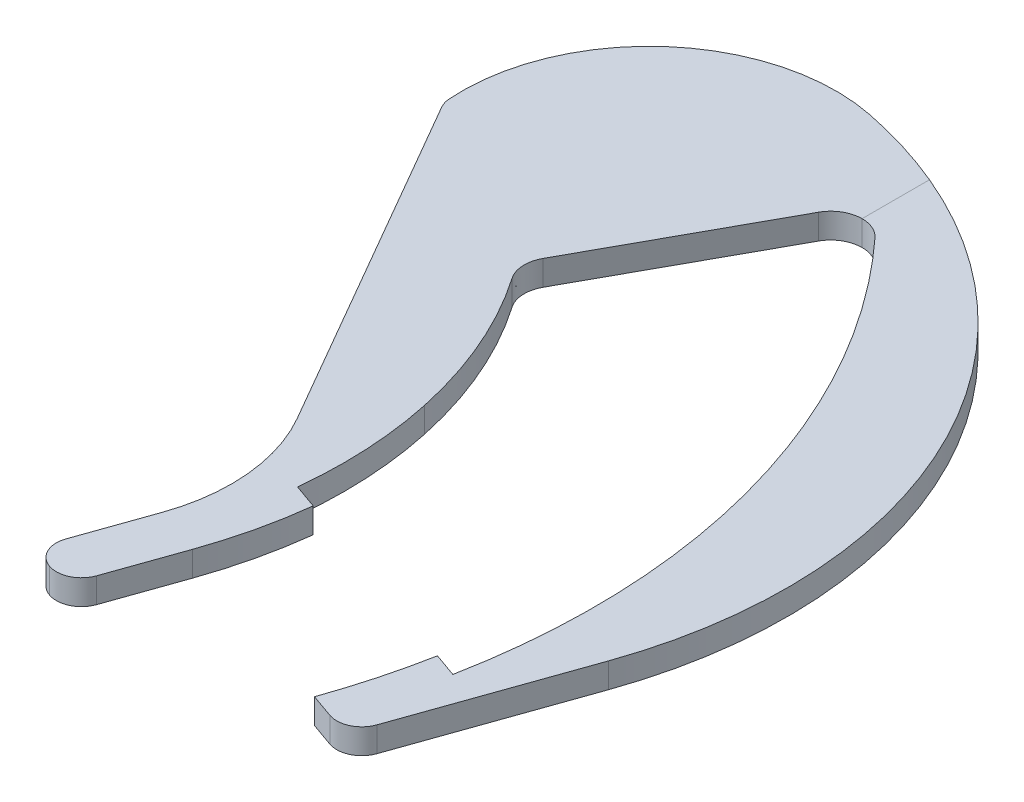
SolidWorks part; units mm, degrees
material "Acrylic (Medium-high impact)"
ref_plane "Front Plane" through (0, 0, 0) normal (0, 0, 1) x (1, 0, 0)
ref_plane "Top Plane" through (0, 0, 0) normal (0, 1, 0) x (1, 0, 0)
ref_plane "Right Plane" through (0, 0, 0) normal (1, 0, 0) x (0, 0, -1)
sketch "Sketch1" plane through (0, 0, 0) normal (0, 1, 0) x (1, 0, 0)
  line L59 (-47.4532, 53.4043) -> (-98.2532, 141.3925)
  line L60 (0, 0) -> (27.9445, -9.8615)
  line L61 (0, 0) -> (-43.9505, 15.5099)
  line L62 (-1000, 0) -> (49000, 0) construction
  line L64 (27.9445, -9.8615) -> (72.8551, -25.7103) construction
  line L65 (72.8551, -25.7103) -> (88.7038, 19.2003) construction
  line L66 (27.9445, -9.8615) -> (-207.1917, -676.1663) construction
  line L67 (45.3803, 39.5461) -> (27.9445, -9.8615)
  line L68 (-43.9505, 15.5099) -> (-28.1017, 60.4205) construction
  line L69 (-88.861, 31.3587) -> (-86.5095, 38.0222) construction
  line L70 (53.7407, 188.0768) -> (-24.6782, 188.0768) construction
  line L71 (-43.9505, 15.5099) -> (-88.861, 31.3587) construction
  arc A0 (45.3803, 39.5461) -> (-41.5665, 192.8393) centre (-64.7226, 78.401) ccw
  arc A1 (-98.2532, 141.3925) -> (-41.5665, 192.8393) centre (-50.9898, 146.2689) cw
  arc A2 (-43.9505, 15.5099) -> (-47.4532, 53.4043) centre (-86.8603, 30.6526) ccw
  dimension "D5" = 4.7625
  dimension "D2" = 45.5033
  dimension "D11" = 37.8944
  dimension "D12" = 7.0663
  dimension "D8" = 52.3939
  dimension "D9" = 46.6069
  dimension "D4" = 19.438
  dimension "D7" = 116.7576
  dimension "D6" = 47.5143
  dimension "D10" = 29.6335
  dimension "D3" = 101.6
  dimension "D1" = 47.625
  dimension "D13" = 78.4189
extrude "Boss-Extrude1" add sketch "Sketch1" along normal blind 6.35
ref_plane "Plane1" through (-8.003, 0, -2.8242) normal (0.943, 0, 0.3328) x (0.3328, 0, -0.943)
sketch "Sketch2" plane through (0, 0, 0) normal (0, 1, 0) x (1, 0, 0)
  line L0 (-43.9505, 15.5099) -> (27.9445, -9.8615) construction
  point P2 (-8.003, 2.8242)
  point P3 (-8.003, 2.8242)
  line B0 (-29.2366, 81.4276) -> (15.5744, 98.7927)
  line B1 (11.6131, 92.147) -> (-21.6985, 79.2205)
  line B2 (-25.5648, 59.5252) -> (22.719, 42.4861)
  line B3 (28.6163, 16.8366) -> (22.5595, 18.974)
  line B4 (-26.1738, 36.1718) -> (-32.322, 38.3415)
  line B5 (-25.1489, 88.1192) -> (10.3796, 101.8872)
  line B6 (-51.3926, 119.7839) -> (-26.6046, 164.8774)
  line B7 (-44.0739, 123.2114) -> (-25.3, 157.3642)
  line B8 (-31.9553, 11.2769) -> (15.9493, -5.6285)
  line B9 (22.5595, 18.974) -> (-26.1738, 36.1718)
  arc B10 (-27.5994, 72.1341) -> (-28.8269, 77.6086) centre (-28.1238, 74.8914) ccw
  arc B11 (-29.2366, 81.4276) -> (-29.7842, 81.1914) centre (-26.3685, 74.0264) ccw
  arc B12 (17.8172, 99.3043) -> (15.5744, 98.7927) centre (18.4425, 91.3914) ccw
  arc B13 (18.8456, 95.8956) -> (20.3121, 90.5015) centre (19.3312, 93.1313) ccw
  arc B14 (13.6735, 91.1895) -> (20.9914, 87.3846) centre (19.3312, 93.1313) ccw
  arc B15 (-27.0229, 69.0118) -> (-22.587, 77.1552) centre (-28.1238, 74.8914) ccw
  arc B16 (20.3121, 90.5015) -> (18.8456, 95.8956) centre (19.3312, 93.1313) ccw
  arc B17 (28.6163, 16.8366) -> (26.1201, 93.4056) centre (-140.6727, 49.6428) ccw
  arc B18 (26.9496, 45.3998) -> (22.9664, 86.2145) centre (-140.6737, 49.643) ccw
  arc B19 (-28.827, 77.6085) -> (-27.5994, 72.1341) centre (-28.1238, 74.8914) ccw
  arc B20 (-27.6639, 62.1695) -> (-25.8173, 59.6267) centre (-24.5082, 62.5193) ccw
  arc B21 (-32.322, 38.3415) -> (-34.1314, 72.3702) centre (-140.6727, 49.6428) ccw
  arc B22 (10.3796, 101.8872) -> (14.8753, 112.2511) centre (7.5115, 109.2884) ccw
  arc B23 (-35.3684, 92.527) -> (-25.1489, 88.1192) centre (-28.017, 95.5204) ccw
  arc B24 (-43.0735, 110.8831) -> (-43.464, 121.0781) centre (-46.3902, 115.8611) ccw
  arc B25 (15.9493, -5.6285) -> (22.5595, 18.974) centre (-140.6729, 49.642) ccw
  arc B26 (-31.9553, 11.2769) -> (-26.1738, 36.1718) centre (-140.6725, 49.6436) ccw
  spline B27 degree 3 poles (17.8172, 99.3043) (18.2808, 99.3409) (18.7407, 99.3366) (19.6534, 99.2495) (20.1077, 99.1662) (21.0026, 98.9191) (21.4331, 98.7584) (22.0543, 98.4634) (22.2573, 98.356) (22.6549, 98.123) (22.8504, 97.9967) (23.4171, 97.5941) (23.7667, 97.2963) (24.2502, 96.807) (24.4045, 96.6367) (24.699, 96.2816) (24.84, 96.0958) (25.2347, 95.5249) (25.4616, 95.126) (25.8451, 94.2925) (26.0022, 93.8555) (26.1202, 93.4057) knots 0 0 0 0 0.125 0.125 0.25 0.25 0.375 0.375 0.4375 0.4375 0.5 0.5 0.625 0.625 0.6875 0.6875 0.75 0.75 0.875 0.875 1 1 1 1
  spline B28 degree 3 poles (-34.1313, 72.3702) (-34.3175, 73.2427) (-34.3554, 74.1214) (-34.1352, 75.8909) (-33.8828, 76.7344) (-33.0952, 78.3332) (-32.5797, 79.0482) (-31.6292, 79.9869) (-31.2886, 80.2706) (-30.5679, 80.7764) (-30.1868, 80.9994) (-29.7842, 81.1914) knots 0 0 0 0 0.25 0.25 0.5 0.5 0.75 0.75 0.875 0.875 1 1 1 1
  spline B29 degree 2 poles (-26.6046, 164.8774) (-26.1506, 165.7033) (-25.5154, 166.4003) (-24.879, 167.0987) (-24.0954, 167.6288) (-23.3138, 168.1575) (-22.4289, 168.4884) (-21.5475, 168.8181) (-20.6123, 168.9325) (-19.6749, 169.0473) (-18.7356, 168.9385) (-17.7973, 168.83) (-16.9097, 168.5037) (-16.0263, 168.179) (-15.2426, 167.656) (-14.4528, 167.129) (-13.8094, 166.4302) knots 0 0 0 0.125 0.125 0.25 0.25 0.375 0.375 0.5 0.5 0.625 0.625 0.75 0.75 0.875 0.875 1 1 1
  spline B30 degree 3 poles (26.1163, 93.4018) (24.3249, 100.238) (22.1302, 106.9013) (16.9621, 119.8936) (13.988, 126.2224) (9.777, 133.9217) (8.91, 135.4509) (7.1262, 138.488) (6.208, 139.9978) (3.3864, 144.4804) (1.4239, 147.3946) (-4.7015, 155.9203) (-9.1008, 161.3163) (-13.8094, 166.4302) knots 0 0 0 0 0.25 0.25 0.5 0.5 0.5625 0.5625 0.625 0.625 0.75 0.75 1 1 1 1
  spline B31 degree 3 poles (-13.3161, 158.7044) (-10.6959, 155.6457) (-8.187, 152.4937) (-4.3894, 147.3517) (-3.0295, 145.4278) (-0.3835, 141.5096) (0.9037, 139.513) (3.3926, 135.4673) (4.5925, 133.4211) (6.8969, 129.2936) (8.0024, 127.2107) (11.1817, 120.9021) (13.1195, 116.615) (14.8753, 112.2511) knots 0.074143 0.074143 0.074143 0.074143 0.222946 0.222946 0.309438 0.309438 0.395929 0.395929 0.48242 0.48242 0.568911 0.568911 0.741894 0.741894 0.741894 0.741894
  spline B32 degree 3 poles (-35.3684, 92.527) (-36.6307, 95.6269) (-38.0226, 98.6534) (-40.7885, 104.036) (-42.1249, 106.4194) (-43.5456, 108.7522) knots 0.447067 0.447067 0.447067 0.447067 0.670186 0.670186 0.854821 0.854821 0.854821 0.854821
  spline B33 degree 2 poles (-50.9715, 111.4537) (-51.5973, 112.3613) (-51.9523, 113.4056) (-52.3075, 114.4507) (-52.3641, 115.5542) (-52.4206, 116.6572) (-52.1734, 117.7348) (-51.9261, 118.8136) (-51.3926, 119.7839) knots 0 0 0 0.25 0.25 0.5 0.5 0.75 0.75 1 1 1
  spline B34 degree 3 poles (-50.9715, 111.4537) (-48.9588, 108.5346) (-47.0926, 105.5237) (-43.6539, 99.3178) (-42.0816, 96.1226) (-39.9504, 91.1875) (-39.2781, 89.5185) (-38.0214, 86.161) (-37.4355, 84.4688) (-36.3479, 81.058) (-35.8463, 79.3393) (-34.9276, 75.8754) (-34.5102, 74.1291) (-34.136, 72.3718) knots 0 0 0 0 0.25 0.25 0.5 0.5 0.625 0.625 0.75 0.75 0.875 0.875 1 1 1 1
sketch_block_instance "Ramp Geometry-1"
sketch_block "Ramp Geometry"
sketch "Sketch5" plane through (0, 6.35, 0) normal (0, 1, 0) x (1, 0, 0)
  line L1 (28.6163, 16.8366) -> (22.5595, 18.974) construction
  line L2 (-31.9553, 11.2769) -> (15.9493, -5.6285) construction
  line L3 (-26.1738, 36.1718) -> (-32.322, 38.3415) construction
  line L4 (-29.2366, 81.4276) -> (15.5744, 98.7927)
  line L5 (28.6163, 16.8366) -> (22.5595, 18.974)
  line L6 (-31.9553, 11.2769) -> (15.9493, -5.6285)
  line L7 (-26.1738, 36.1718) -> (-32.322, 38.3415)
  arc A2 (28.6163, 16.8366) -> (26.1201, 93.4056) centre (-140.6727, 49.6428) ccw construction
  arc A3 (15.9493, -5.6285) -> (22.5595, 18.974) centre (-140.6729, 49.642) ccw construction
  arc A4 (-31.9553, 11.2769) -> (-26.1738, 36.1718) centre (-140.6725, 49.6436) ccw construction
  arc A5 (-32.322, 38.3415) -> (-34.1314, 72.3702) centre (-140.6727, 49.6428) ccw construction
  arc A6 (-34.1314, 72.3702) -> (-29.2366, 81.4276) centre (-26.3759, 74.0303) cw
  arc A7 (26.1201, 93.4056) -> (15.5744, 98.7927) centre (18.4429, 91.3925) ccw
  arc A8 (28.6163, 16.8366) -> (26.1201, 93.4056) centre (-140.6727, 49.6428) ccw
  arc A9 (15.9493, -5.6285) -> (22.5595, 18.974) centre (-140.6729, 49.642) ccw
  arc A10 (-31.9553, 11.2769) -> (-26.1738, 36.1718) centre (-140.6725, 49.6436) ccw
  arc A11 (-32.322, 38.3415) -> (-34.1314, 72.3702) centre (-140.6727, 49.6428) ccw
  spline S2 degree 3 poles (17.8172, 99.3043) (18.2808, 99.3409) (18.7407, 99.3366) (19.6534, 99.2495) (20.1077, 99.1662) (21.0026, 98.9191) (21.4331, 98.7584) (22.0543, 98.4634) (22.2573, 98.356) (22.6549, 98.123) (22.8504, 97.9967) (23.4171, 97.5941) (23.7667, 97.2963) (24.2502, 96.807) (24.4045, 96.6367) (24.699, 96.2816) (24.84, 96.0958) (25.2347, 95.5249) (25.4616, 95.126) (25.8451, 94.2925) (26.0022, 93.8555) (26.1202, 93.4057) knots 0 0 0 0 0.125 0.125 0.25 0.25 0.375 0.375 0.4375 0.4375 0.5 0.5 0.625 0.625 0.6875 0.6875 0.75 0.75 0.875 0.875 1 1 1 1 construction
  spline S3 degree 3 poles (-34.1313, 72.3702) (-34.3175, 73.2427) (-34.3554, 74.1214) (-34.1352, 75.8909) (-33.8828, 76.7344) (-33.0952, 78.3332) (-32.5797, 79.0482) (-31.6292, 79.9869) (-31.2886, 80.2706) (-30.5679, 80.7764) (-30.1868, 80.9994) (-29.7842, 81.1914) knots 0 0 0 0 0.25 0.25 0.5 0.5 0.75 0.75 0.875 0.875 1 1 1 1 construction
extrude "Cut-Extrude1" cut sketch "Sketch5" against normal through all
sketch "Sketch6" plane through (0, 6.35, 0) normal (0, 1, 0) x (1, 0, 0)
  line L0 (-34.136, 72.3718) -> (26.1163, 93.4018)
  line L2 (-51.3926, 119.7839) -> (-26.6046, 164.8774) construction
  line L3 (-51.3926, 119.7839) -> (-26.6046, 164.8774)
  spline S0 degree 3 poles (-1429.6439, -1247.1312) (-221.2393, -482.3872) (103.2117, -96.9361) (16.9621, 119.8936) (13.988, 126.2224) (9.777, 133.9217) (8.91, 135.4509) (7.1262, 138.488) (6.208, 139.9978) (3.3864, 144.4804) (1.4239, 147.3946) (-186.5695, 409.0534) (-1027.0588, 71.2021) (-1932.3264, -325.7002) knots -7.844512 -7.844512 -7.844512 -7.844512 0.25 0.25 0.5 0.5 0.5625 0.5625 0.625 0.625 0.75 0.75 12.134027 12.134027 12.134027 12.134027 only from (26.1163, 93.4018) to (-13.8094, 166.4302) construction
  spline S1 degree 2 poles (1493.7423, -1132.5068) (-85.9486, 100.0778) (-25.5154, 166.4003) (-24.879, 167.0987) (-24.0954, 167.6288) (-23.3138, 168.1575) (-22.4289, 168.4884) (-21.5475, 168.8181) (-20.6123, 168.9325) (-19.6749, 169.0473) (-18.7356, 168.9385) (-17.7973, 168.83) (-16.9097, 168.5037) (-16.0263, 168.179) (-15.2426, 167.656) (59.3198, 117.902) (-1170.3473, -1463.6448) knots -11.768568 -11.768568 -11.768568 0.125 0.125 0.25 0.25 0.375 0.375 0.5 0.5 0.625 0.625 0.75 0.75 0.875 0.875 12.67723 12.67723 12.67723 only from (-26.6046, 164.8774) to (-13.8094, 166.4302) construction
  spline S2 degree 2 poles (1805.4899, 851.8486) (-23.0142, 28.2719) (-51.9523, 113.4056) (-52.3075, 114.4507) (-52.3641, 115.5542) (-52.4206, 116.6572) (-52.1734, 117.7348) (-32.0934, 205.297) (1872.6772, -421.0496) knots -20.129916 -20.129916 -20.129916 0.25 0.25 0.5 0.5 0.75 0.75 21.042954 21.042954 21.042954 only from (-50.9715, 111.4537) to (-51.3926, 119.7839) construction
  spline S3 degree 3 poles (-1984.765, -331.989) (-829.3418, 131.8338) (-152.4686, 295.6978) (-43.6539, 99.3178) (-42.0816, 96.1226) (-39.9504, 91.1875) (-39.2781, 89.5185) (-38.0214, 86.161) (-37.4355, 84.4688) (-36.3479, 81.058) (-35.8463, 79.3393) (3.3124, -68.2971) (-256.1389, -315.9435) (-1530.5486, 1352.6355) knots -15.321981 -15.321981 -15.321981 -15.321981 0.25 0.25 0.5 0.5 0.625 0.625 0.75 0.75 0.875 0.875 11.405236 11.405236 11.405236 11.405236 only from (-50.9715, 111.4537) to (-34.136, 72.3718) construction
  spline S4 degree 3 poles (26.1163, 93.4018) (24.3249, 100.238) (22.1302, 106.9013) (16.9621, 119.8936) (13.988, 126.2224) (9.777, 133.9217) (8.91, 135.4509) (7.1262, 138.488) (6.208, 139.9978) (3.3864, 144.4804) (1.4239, 147.3946) (-4.7015, 155.9203) (-9.1008, 161.3163) (-13.8094, 166.4302) knots 0 0 0 0 0.25 0.25 0.5 0.5 0.5625 0.5625 0.625 0.625 0.75 0.75 1 1 1 1
  spline S5 degree 2 poles (-26.6046, 164.8774) (-26.1506, 165.7033) (-25.5154, 166.4003) (-24.879, 167.0987) (-24.0954, 167.6288) (-23.3138, 168.1575) (-22.4289, 168.4884) (-21.5475, 168.8181) (-20.6123, 168.9325) (-19.6749, 169.0473) (-18.7356, 168.9385) (-17.7973, 168.83) (-16.9097, 168.5037) (-16.0263, 168.179) (-15.2426, 167.656) (-14.4528, 167.129) (-13.8094, 166.4302) knots 0 0 0 0.125 0.125 0.25 0.25 0.375 0.375 0.5 0.5 0.625 0.625 0.75 0.75 0.875 0.875 1 1 1
  spline S6 degree 2 poles (-50.9715, 111.4537) (-51.5973, 112.3613) (-51.9523, 113.4056) (-52.3075, 114.4507) (-52.3641, 115.5542) (-52.4206, 116.6572) (-52.1734, 117.7348) (-51.9261, 118.8136) (-51.3926, 119.7839) knots 0 0 0 0.25 0.25 0.5 0.5 0.75 0.75 1 1 1
  spline S7 degree 3 poles (-50.9715, 111.4537) (-48.9588, 108.5346) (-47.0926, 105.5237) (-43.6539, 99.3178) (-42.0816, 96.1226) (-39.9504, 91.1875) (-39.2781, 89.5185) (-38.0214, 86.161) (-37.4355, 84.4688) (-36.3479, 81.058) (-35.8463, 79.3393) (-34.9276, 75.8754) (-34.5102, 74.1291) (-34.136, 72.3718) knots 0 0 0 0 0.25 0.25 0.5 0.5 0.625 0.625 0.75 0.75 0.875 0.875 1 1 1 1
extrude "Cut-Extrude2" cut sketch "Sketch6" against normal through all
sketch "Sketch7" plane through (0, 0, 0) normal (0, 1, 0) x (1, 0, 0)
  line L0 (-43.9505, 15.5099) -> (-52.4031, -8.4424)
  line L1 (-52.4031, -8.4424) -> (-40.4081, -12.6754)
  line L2 (-40.4081, -12.6754) -> (-31.9553, 11.2769)
  line L3 (-31.9553, 11.2769) -> (-43.9505, 15.5099)
  arc A0 (-31.9553, 11.2769) -> (-26.1738, 36.1718) centre (-140.6725, 49.6436) ccw construction
  arc A1 (-43.9505, 15.5099) -> (-47.4532, 53.4043) centre (-86.8603, 30.6526) ccw construction
  dimension "D1" = 25.4
extrude "Boss-Extrude2" add sketch "Sketch7" along normal up to surface (6.35 mm away) up to face at (-15.4124, 6.35, -73.243)
fillet "Fillet1" radius 6.35 4 edges at (-98.2532, 3.175, -141.3925) (27.9445, 3.175, 9.8615) (-40.4081, 3.175, 12.6754) (-52.4031, 3.175, 8.4424)
sketch "Sketch8" plane through (0, 6.35, 0) normal (0, 1, 0) x (1, 0, 0)
  line L0 (-19.6492, 186.1077) -> (-19.6492, 168.9914)
  line L1 (8.9369, 168.9914) -> (-9.261, 168.9914) construction
  arc A0 (45.3803, 39.5461) -> (-41.5665, 192.8393) centre (-64.7226, 78.401) ccw construction
  arc A1 (-41.5665, 192.8393) -> (-98.3844, 142.8985) centre (-50.9898, 146.2689) ccw construction
  spline S0 degree 2 poles (-13.8094, 166.4302) (-14.4528, 167.129) (-15.2426, 167.656) (-16.0263, 168.179) (-16.9097, 168.5037) (-17.7973, 168.83) (-18.7356, 168.9385) (-19.6749, 169.0473) (-20.6123, 168.9325) (-21.5475, 168.8181) (-22.4289, 168.4884) (-23.3138, 168.1575) (-24.0954, 167.6288) (-24.879, 167.0987) (-25.5154, 166.4003) (-26.1506, 165.7033) (-26.6046, 164.8774) knots 0 0 0 0.125 0.125 0.25 0.25 0.375 0.375 0.5 0.5 0.625 0.625 0.75 0.75 0.875 0.875 1 1 1 construction
  point P9 (0, 0)
  point P13 (-1.0677, 176.2805)
  point P14 (-21.9048, 168.664)
split "Split1" trim tools "Sketch8" bodies to split 111 resulting bodies 114 115
